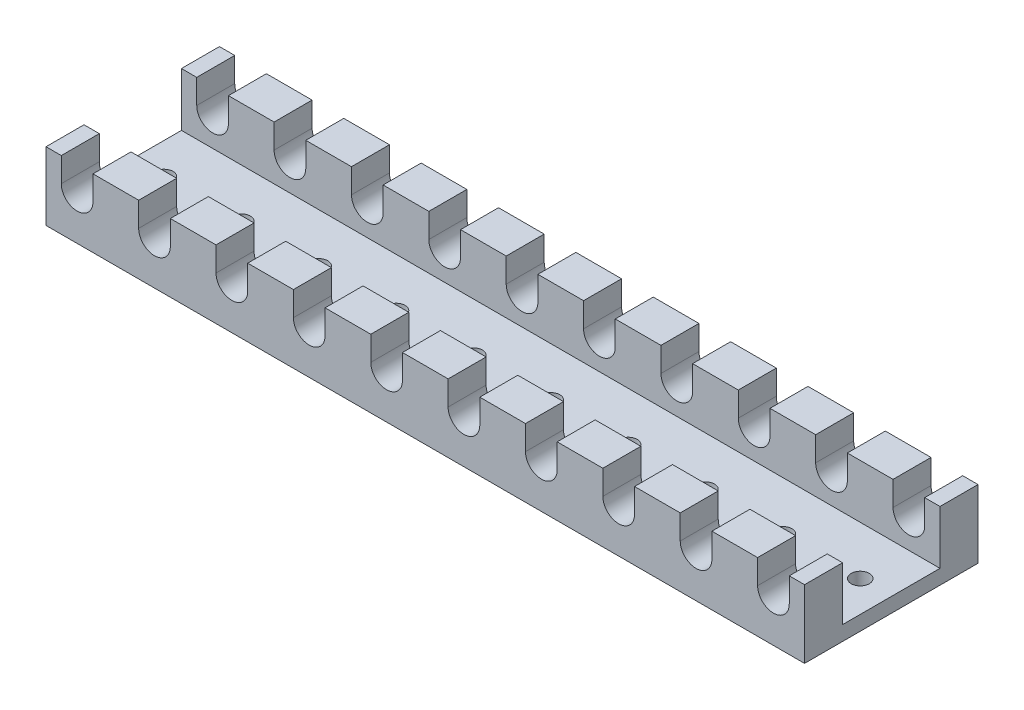
SolidWorks part; units mm, degrees
material "ABS"
ref_plane "Ground_Plane" through (0, 0, 0) normal (0, 0, 1) x (1, 0, 0)
ref_plane "VehicleCentre_Plane" through (0, 0, 0) normal (0, 1, 0) x (1, 0, 0)
ref_plane "FrontAxle_Plane" through (0, 0, 0) normal (1, 0, 0) x (0, 0, -1)
sketch "Sketch1" plane through (0, 0, 0) normal (0, 1, 0) x (1, 0, 0)
  line L1 (77.85, 17.8) -> (-77.85, 17.8)
  line L2 (77.85, 17.8) -> (77.85, -17.8)
  line L3 (77.85, -17.8) -> (-77.85, -17.8)
  line L4 (-77.85, 17.8) -> (-77.85, -17.8)
  line L5 (77.85, 17.8) -> (-77.85, -17.8) construction
  line L6 (77.85, -17.8) -> (-77.85, 17.8) construction
  point P0 (0, 0)
  dimension "D1" = 155.7
  dimension "D2" = 35.6
extrude "Boss-Extrude1" add sketch "Sketch1" along normal blind 14
sketch "Sketch3" plane through (0, 14, 0) normal (0, 1, 0) x (1, 0, 0)
  line L0 (-71.4375, 0) -> (-55.5575, 0) construction
  circle A0 centre (-71.4375, 0) radius 1.85
  circle A1 centre (-55.5575, 0) radius 1.85
  circle A2 centre (-39.6775, 0) radius 1.85
  circle A3 centre (-23.7975, 0) radius 1.85
  circle A4 centre (-7.9175, 0) radius 1.85
  circle A5 centre (7.9625, 0) radius 1.85
  circle A6 centre (23.8425, 0) radius 1.85
  circle A7 centre (39.7225, 0) radius 1.85
  circle A8 centre (55.6025, 0) radius 1.85
  circle A9 centre (71.4825, 0) radius 1.85
  dimension "D2" = 3.7
  dimension "D1" = 71.4375
  dimension "D4" = 15.88
  dimension "D3" = 10
extrude "Cut-Extrude1" cut sketch "Sketch3" against normal through all
sketch "Sketch4" plane through (-77.85, 0, 0) normal (-1, 0, 0) x (0, 0, 1)
  line L0 (-17.8, 14) -> (17.8, 14) construction
  line L1 (-10, 14) -> (10, 14)
  line L2 (-10, 14) -> (-10, 3)
  line L3 (-10, 3) -> (10, 3)
  line L4 (10, 14) -> (10, 3)
  line L5 (-10, 14) -> (10, 3) construction
  line L6 (-10, 3) -> (10, 14) construction
  line L7 (-17.8, 0) -> (17.8, 0) construction
  point P4 (0, 8.5)
  dimension "D1" = 3
  dimension "D2" = 20
extrude "Cut-Extrude2" cut sketch "Sketch4" against normal through all
sketch "Sketch5" plane through (0, 0, 17.8) normal (0, 0, 1) x (1, 0, 0)
  line L0 (-74.71, 9) -> (-74.71, 15)
  line L1 (-74.71, 15) -> (-68.21, 15)
  line L2 (-68.21, 15) -> (-68.21, 9)
  line L3 (-77.85, 14) -> (77.85, 14) construction
  line L5 (-77.85, 0) -> (77.85, 0) construction
  line L6 (-52.33, 15) -> (-52.33, 9)
  line L7 (-58.83, 15) -> (-52.33, 15)
  line L8 (-58.83, 9) -> (-58.83, 15)
  line L9 (-36.45, 15) -> (-36.45, 9)
  line L10 (-42.95, 15) -> (-36.45, 15)
  line L11 (-42.95, 9) -> (-42.95, 15)
  line L12 (-20.57, 15) -> (-20.57, 9)
  line L13 (-27.07, 15) -> (-20.57, 15)
  line L14 (-27.07, 9) -> (-27.07, 15)
  line L15 (-4.69, 15) -> (-4.69, 9)
  line L16 (-11.19, 15) -> (-4.69, 15)
  line L17 (-11.19, 9) -> (-11.19, 15)
  line L18 (11.19, 15) -> (11.19, 9)
  line L19 (4.69, 15) -> (11.19, 15)
  line L20 (4.69, 9) -> (4.69, 15)
  line L21 (27.07, 15) -> (27.07, 9)
  line L22 (20.57, 15) -> (27.07, 15)
  line L23 (20.57, 9) -> (20.57, 15)
  line L24 (42.95, 15) -> (42.95, 9)
  line L25 (36.45, 15) -> (42.95, 15)
  line L26 (36.45, 9) -> (36.45, 15)
  line L27 (58.83, 15) -> (58.83, 9)
  line L28 (52.33, 15) -> (58.83, 15)
  line L29 (52.33, 9) -> (52.33, 15)
  line L30 (74.71, 15) -> (74.71, 9)
  line L31 (68.21, 15) -> (74.71, 15)
  line L32 (68.21, 9) -> (68.21, 15)
  line L33 (-74.71, 9) -> (-58.83, 9) construction
  arc A0 (-74.71, 9) -> (-68.21, 9) centre (-71.46, 9) ccw
  arc A1 (-58.83, 9) -> (-52.33, 9) centre (-55.58, 9) ccw
  arc A2 (-42.95, 9) -> (-36.45, 9) centre (-39.7, 9) ccw
  arc A3 (-27.07, 9) -> (-20.57, 9) centre (-23.82, 9) ccw
  arc A4 (-11.19, 9) -> (-4.69, 9) centre (-7.94, 9) ccw
  arc A5 (4.69, 9) -> (11.19, 9) centre (7.94, 9) ccw
  arc A6 (20.57, 9) -> (27.07, 9) centre (23.82, 9) ccw
  arc A7 (36.45, 9) -> (42.95, 9) centre (39.7, 9) ccw
  arc A8 (52.33, 9) -> (58.83, 9) centre (55.58, 9) ccw
  arc A9 (68.21, 9) -> (74.71, 9) centre (71.46, 9) ccw
  point P11 (0, 0)
  dimension "D1" = 3.25
  dimension "D2" = 1
  dimension "D3" = 5
  dimension "D4" = 71.46
  dimension "D6" = 15.88
  dimension "D5" = 10
extrude "Cut-Extrude3" cut sketch "Sketch5" against normal through all
equation "\"D4@Sketch5\"=15.88*4.5"
